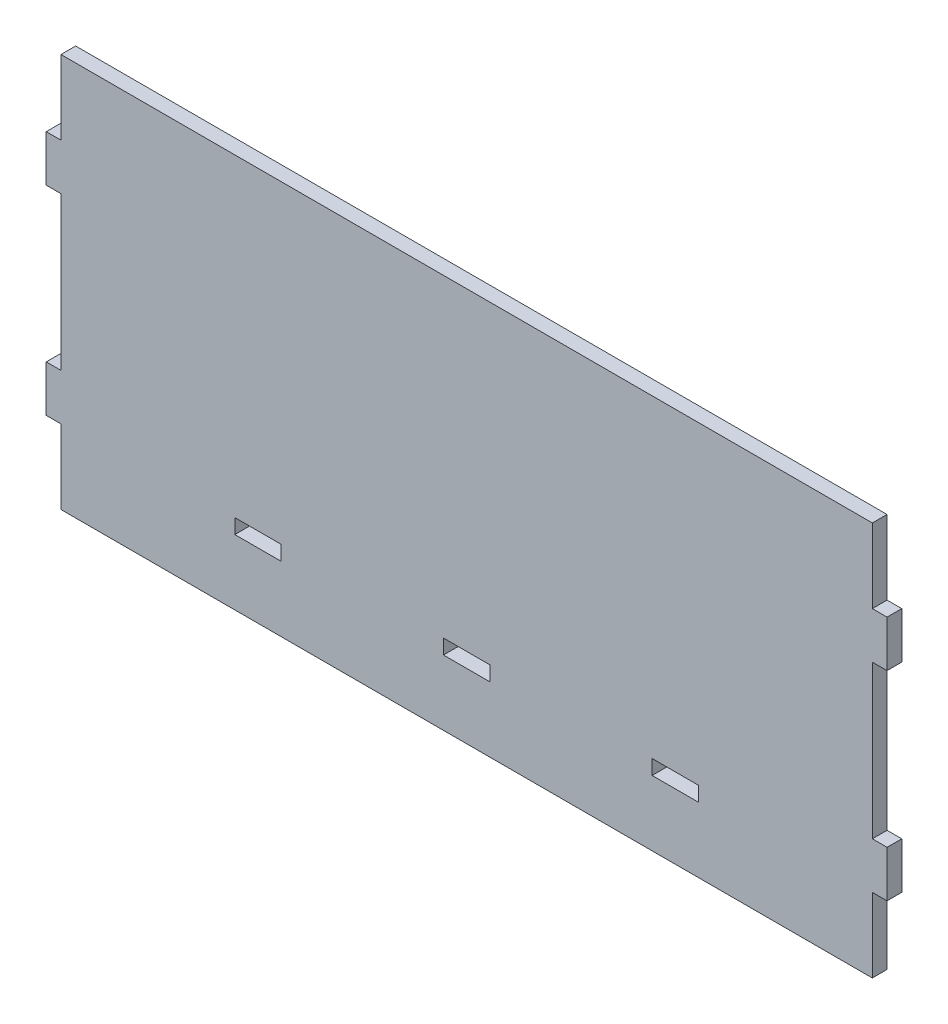
SolidWorks part; units mm, degrees
ref_plane "Alzado" through (0, 0, 0) normal (0, 0, 1) x (1, 0, 0)
ref_plane "Planta" through (0, 0, 0) normal (0, 1, 0) x (1, 0, 0)
ref_plane "Vista lateral" through (0, 0, 0) normal (1, 0, 0) x (0, 0, -1)
sketch "Croquis1" plane through (0, 0, 0) normal (0, 0, 1) x (1, 0, 0)
  line L1 (-156.35, 150) -> (193.65, 150)
  line L2 (-156.35, 150) -> (-156.35, -20)
  line L3 (-156.35, -20) -> (193.65, -20)
  line L4 (193.65, 150) -> (193.65, -20)
  dimension "D1" = 170
  dimension "D2" = 350
extrude "Saliente-Extruir1" add sketch "Croquis1" along normal blind 6.35
sketch "Croquis2" plane through (-156.35, 0, 0) normal (-1, 0, 0) x (0, 0, 1)
  line L0 (0, 150) -> (0, -20) construction
  line L1 (0, 118) -> (6.35, 118)
  line L2 (0, 118) -> (0, 98)
  line L3 (0, 98) -> (6.35, 98)
  line L4 (6.35, 118) -> (6.35, 98)
  line L5 (6.35, 150) -> (6.35, -20) construction
  line L6 (6.35, -20) -> (0, -20) construction
  line L7 (0, 32) -> (6.35, 32)
  line L8 (0, 32) -> (0, 12)
  line L9 (0, 12) -> (6.35, 12)
  line L10 (6.35, 32) -> (6.35, 12)
  line L11 (6.35, 150) -> (0, 150) construction
  point P16 (3.175, 150)
  dimension "D1" = 20
  dimension "D2" = 20
  dimension "D3" = 32
  dimension "D4" = 32
extrude "Saliente-Extruir2" add sketch "Croquis2" along normal blind 6.35
ref_plane "Plano1" through (18.65, 0, 0) normal (1, 0, 0) x (0, 0, -1)
mirror "Simetría1" about plane through (18.65, 0, 0) normal (1, 0, 0) of "Saliente-Extruir2"
sketch "Croquis4" plane through (0, 0, 6.35) normal (0, 0, 1) x (1, 0, 0)
  line L0 (-156.35, -20) -> (193.65, -20) construction
  line L1 (28.65, 8.16) -> (8.65, 8.16)
  line L2 (28.65, 8.16) -> (28.65, 14.51)
  line L3 (28.65, 14.51) -> (8.65, 14.51)
  line L4 (8.65, 8.16) -> (8.65, 14.51)
  line L13 (118.65, 8.16) -> (98.65, 8.16)
  line L14 (118.65, 8.16) -> (118.65, 14.51)
  line L15 (118.65, 14.51) -> (98.65, 14.51)
  line L16 (98.65, 8.16) -> (98.65, 14.51)
  line L17 (-61.35, 8.16) -> (-81.35, 8.16)
  line L18 (-61.35, 8.16) -> (-61.35, 14.51)
  line L19 (-61.35, 14.51) -> (-81.35, 14.51)
  line L20 (-81.35, 8.16) -> (-81.35, 14.51)
  point P6 (18.65, 14.51)
  point P7 (18.65, -20)
  dimension "D1" = 20
  dimension "D2" = 6.35
  dimension "D3" = 28.16
extrude "Cortar-Extruir1" cut sketch "Croquis4" against normal blind 10
